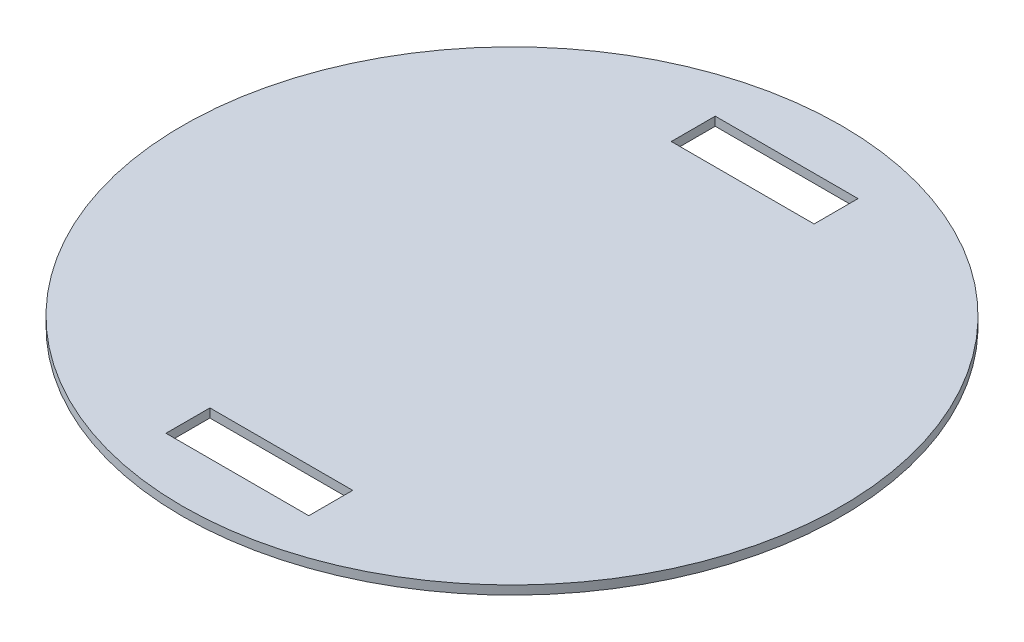
SolidWorks part; units mm, degrees
material "Verre"
ref_plane "Plan de face" through (0, 0, 0) normal (0, 0, 1) x (1, 0, 0)
ref_plane "Plan de dessus" through (0, 0, 0) normal (0, 1, 0) x (1, 0, 0)
ref_plane "Plan de droite" through (0, 0, 0) normal (1, 0, 0) x (0, 0, -1)
sketch "Esquisse2" plane through (0, 0, 0) normal (0, 1, 0) x (1, 0, 0)
  circle A0 centre (0, 0) radius 150
  dimension "D1" = 300
extrude "Boss.-Extru.1" add sketch "Esquisse2" against normal blind 4
sketch "Esquisse4" plane through (0, 0, 0) normal (0, 1, 0) x (1, 0, 0)
  line L0 (0, -150) -> (0, 150) construction
  line L1 (-32.5, -125) -> (32.5, -125)
  line L2 (-32.5, -125) -> (-32.5, -105)
  line L3 (-32.5, -105) -> (32.5, -105)
  line L4 (32.5, -125) -> (32.5, -105)
  line L5 (-32.5, 105) -> (32.5, 105)
  line L6 (-32.5, 105) -> (-32.5, 125)
  line L7 (-32.5, 125) -> (32.5, 125)
  line L8 (32.5, 105) -> (32.5, 125)
  circle A2 centre (0, 0) radius 150 construction
  point P13 (0, -105)
  point P14 (0, 105)
  dimension "D1" = 20
  dimension "D2" = 65
  dimension "D3" = 65
  dimension "D4" = 20
  dimension "D5" = 25
  dimension "D6" = 25
extrude "Enlèv. mat.-Extru.1" cut sketch "Esquisse4" against normal through all
